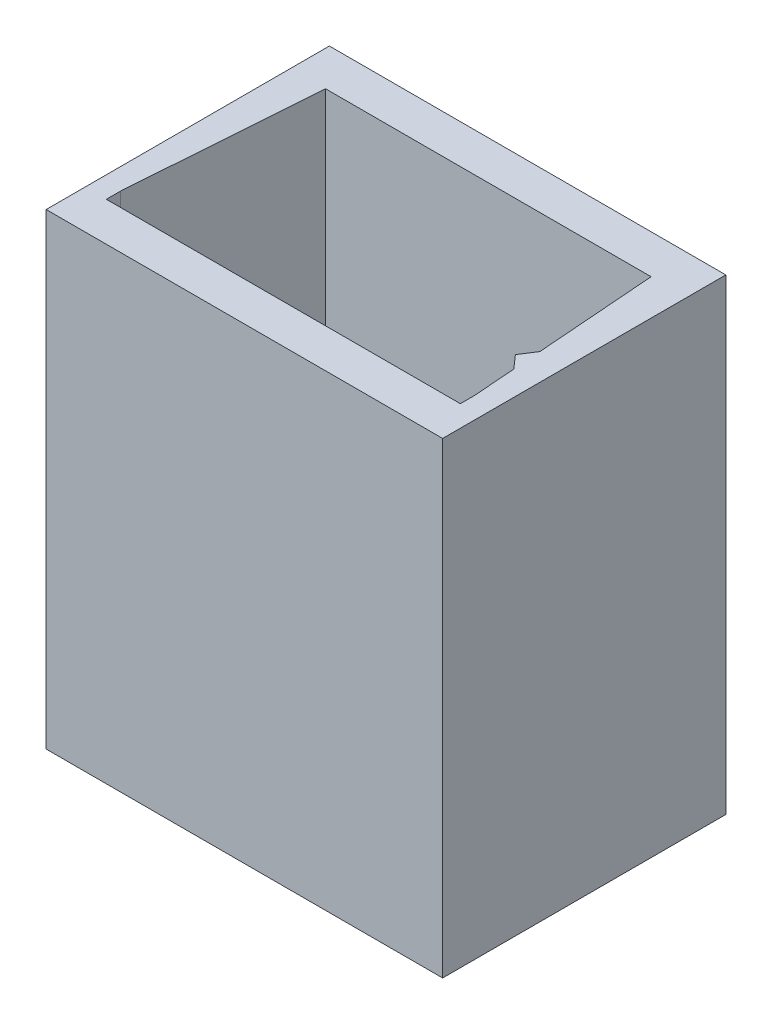
SolidWorks part; units mm, degrees
ref_plane "Plano frontal" through (0, 0, 0) normal (0, 0, 1) x (1, 0, 0)
ref_plane "Plano superior" through (0, 0, 0) normal (0, 1, 0) x (1, 0, 0)
ref_plane "Plano direito" through (0, 0, 0) normal (1, 0, 0) x (0, 0, -1)
sketch "Esboço1" plane through (0, 0, 0) normal (0, 1, 0) x (1, 0, 0)
  line L1 (-28, 20) -> (28, 20)
  line L2 (-28, 20) -> (-28, -20)
  line L3 (-28, -20) -> (28, -20)
  line L4 (28, 20) -> (28, -20)
  dimension "D1" = 56
  dimension "D2" = 40
  dimension "D3" = 20
  dimension "D4" = 28
extrude "Ressalto-extrusão1" add sketch "Esboço1" along normal blind 66
sketch "Esboço2" plane through (0, 66, 0) normal (0, 1, 0) x (1, 0, 0)
  line L0 (-25, -14.5) -> (25, -14.5)
  line L1 (25, -14.5) -> (25, -12.5)
  line L2 (25, -12.5) -> (24.5432, -6.4974)
  line L3 (24.5432, -6.4974) -> (22.8946, -4.618)
  line L4 (22.8946, -4.618) -> (24.2399, -2.5108)
  line L5 (24.2399, -2.5108) -> (22.9455, 14.5)
  line L6 (22.9455, 14.5) -> (-23.0545, 14.5)
  line L7 (-23.0545, 14.5) -> (-25, -12.5)
  line L8 (-25, -12.5) -> (-25, -14.5)
  line L9 (28, -20) -> (28, 20) construction
  line L10 (-28, -20) -> (28, -20) construction
  point P2 (-17.0422, 11.8931)
  point P10 (33.2269, 1.686)
  point P11 (20.4142, -5.3314)
  point P12 (25.9734, -2.0505)
  point P13 (24.0596, 7.2452)
  point P14 (25.9734, -5.5137)
  point P15 (20.7787, -2.6885)
  point P16 (31.6238, 0)
  point P17 (31.6238, -5.8782)
  point P18 (-19.594, -13.4424)
  point P19 (21.2344, -2.6885)
  point P22 (22.2588, 9.8881)
  point P27 (-28, -13.4424)
  dimension "D1" = 50
  dimension "D2" = 46
  dimension "D3" = 27.07
  dimension "D4" = 2
  dimension "D5" = 17.06
  dimension "D6" = 2.5
  dimension "D7" = 6.02
  dimension "D8" = 3
  dimension "D9" = 5.5
  dimension "D10" = 29
extrude "Corte-extrusão1" cut sketch "Esboço2" against normal blind 61
sketch "Esboço10" plane through (0, 0, 0) normal (0, -1, 0) x (1, 0, 0)
  line L0 (-28, -20) -> (-28, 20) construction
  line L1 (-26.7, 18.7) -> (26.7, 18.7)
  line L2 (-26.7, 18.7) -> (-26.7, -18.7)
  line L3 (-26.7, -18.7) -> (26.7, -18.7)
  line L4 (26.7, 18.7) -> (26.7, -18.7)
  line L5 (-28, 20) -> (28, 20) construction
  line L6 (28, 20) -> (28, -20) construction
  line L7 (28, -20) -> (-28, -20) construction
  dimension "D1" = 1.3
  dimension "D2" = 1.3
  dimension "D3" = 1.3
  dimension "D4" = 1.3
extrude "Corte-extrusão2" cut sketch "Esboço10" against normal blind 2.2
sketch "Esboço11" plane through (0, 2.2, 0) normal (0, -1, 0) x (-1, 0, 0)
  line L0 (28, 20) -> (28, -20) construction
  line L3 (26.7, 0) -> (-26.7, 0) construction
  line L4 (26.7, -18.7) -> (26.7, 18.7) construction
  line L5 (-26.7, 18.7) -> (-26.7, -18.7) construction
  line L6 (28, -20) -> (-28, -20) construction
  circle A0 centre (20, -12) radius 2.4
  circle A1 centre (20, -12) radius 3.255
  circle A2 centre (12, -12) radius 3.255
  circle A3 centre (12, -12) radius 2.4
  circle A4 centre (20, -4) radius 3.255
  circle A5 centre (20, -4) radius 2.4
  circle A6 centre (12, -4) radius 3.255
  circle A7 centre (12, -4) radius 2.4
  circle A8 centre (20, 4) radius 3.255
  circle A9 centre (20, 4) radius 2.4
  circle A10 centre (12, 4) radius 3.255
  circle A11 centre (12, 4) radius 2.4
  circle A12 centre (20, 12) radius 3.255
  circle A13 centre (20, 12) radius 2.4
  circle A14 centre (12, 12) radius 3.255
  circle A15 centre (12, 12) radius 2.4
  circle A16 centre (4, -12) radius 3.255
  circle A17 centre (4, -12) radius 2.4
  circle A18 centre (-4, -12) radius 3.255
  circle A19 centre (-4, -12) radius 2.4
  circle A20 centre (-12, -12) radius 3.255
  circle A21 centre (-12, -12) radius 2.4
  circle A22 centre (-20, -12) radius 3.255
  circle A23 centre (-20, -12) radius 2.4
  circle A24 centre (4, -4) radius 3.255
  circle A25 centre (4, -4) radius 2.4
  circle A26 centre (-4, -4) radius 3.255
  circle A27 centre (-4, -4) radius 2.4
  circle A28 centre (-12, -4) radius 3.255
  circle A29 centre (-12, -4) radius 2.4
  circle A30 centre (-20, -4) radius 3.255
  circle A31 centre (-20, -4) radius 2.4
  circle A32 centre (4, 4) radius 3.255
  circle A33 centre (4, 4) radius 2.4
  circle A34 centre (-4, 4) radius 3.255
  circle A35 centre (-4, 4) radius 2.4
  circle A36 centre (-12, 4) radius 3.255
  circle A37 centre (-12, 4) radius 2.4
  circle A38 centre (-20, 4) radius 3.255
  circle A39 centre (-20, 4) radius 2.4
  circle A40 centre (4, 12) radius 3.255
  circle A41 centre (4, 12) radius 2.4
  circle A42 centre (-4, 12) radius 3.255
  circle A43 centre (-4, 12) radius 2.4
  circle A44 centre (-12, 12) radius 3.255
  circle A45 centre (-12, 12) radius 2.4
  circle A46 centre (-20, 12) radius 3.255
  circle A47 centre (-20, 12) radius 2.4
  dimension "D1" = 8
  dimension "D2" = 6.51
  dimension "D3" = 4.8
  dimension "D4" = 8
  dimension "D5" = 6
  dimension "D6" = 4
extrude "Ressalto-extrusão11" add sketch "Esboço11" along normal up to surface (2.2 mm away) up to face at (0, 0, 0)
sketch "Esboço14" plane through (0, 2.2, 0) normal (0, -1, 0) x (1, 0, 0)
  line L0 (-28, 20) -> (28, 20) construction
  line L1 (-24.5, 20) -> (-23.5, 20)
  line L2 (-24.5, 20) -> (-24.5, 18.4)
  line L3 (-24.5, 18.4) -> (-23.5, 18.4)
  line L4 (-23.5, 20) -> (-23.5, 18.4)
  line L5 (-16.5, 20) -> (-15.5, 20)
  line L6 (-15.5, 20) -> (-15.5, 18.4)
  line L7 (-16.5, 18.4) -> (-15.5, 18.4)
  line L8 (-16.5, 20) -> (-16.5, 18.4)
  line L9 (-8.5, 20) -> (-7.5, 20)
  line L10 (-7.5, 20) -> (-7.5, 18.4)
  line L11 (-8.5, 18.4) -> (-7.5, 18.4)
  line L12 (-8.5, 20) -> (-8.5, 18.4)
  line L13 (-0.5, 20) -> (0.5, 20)
  line L14 (0.5, 20) -> (0.5, 18.4)
  line L15 (-0.5, 18.4) -> (0.5, 18.4)
  line L16 (-0.5, 20) -> (-0.5, 18.4)
  line L17 (7.5, 20) -> (8.5, 20)
  line L18 (8.5, 20) -> (8.5, 18.4)
  line L19 (7.5, 18.4) -> (8.5, 18.4)
  line L20 (7.5, 20) -> (7.5, 18.4)
  line L21 (15.5, 20) -> (16.5, 20)
  line L22 (16.5, 20) -> (16.5, 18.4)
  line L23 (15.5, 18.4) -> (16.5, 18.4)
  line L24 (15.5, 20) -> (15.5, 18.4)
  line L25 (23.5, 20) -> (24.5, 20)
  line L26 (24.5, 20) -> (24.5, 18.4)
  line L27 (23.5, 18.4) -> (24.5, 18.4)
  line L28 (23.5, 20) -> (23.5, 18.4)
  line L29 (-16.5, -18.4) -> (-15.5, -18.4)
  line L30 (-15.5, -18.4) -> (-15.5, -20)
  line L31 (-16.5, -20) -> (-15.5, -20)
  line L32 (-16.5, -18.4) -> (-16.5, -20)
  line L33 (-8.5, -18.4) -> (-7.5, -18.4)
  line L34 (-7.5, -18.4) -> (-7.5, -20)
  line L35 (-8.5, -20) -> (-7.5, -20)
  line L36 (-8.5, -18.4) -> (-8.5, -20)
  line L37 (-0.5, -18.4) -> (0.5, -18.4)
  line L38 (0.5, -18.4) -> (0.5, -20)
  line L39 (-0.5, -20) -> (0.5, -20)
  line L40 (-0.5, -18.4) -> (-0.5, -20)
  line L41 (7.5, -18.4) -> (8.5, -18.4)
  line L42 (8.5, -18.4) -> (8.5, -20)
  line L43 (7.5, -20) -> (8.5, -20)
  line L44 (7.5, -18.4) -> (7.5, -20)
  line L45 (15.5, -18.4) -> (16.5, -18.4)
  line L46 (16.5, -18.4) -> (16.5, -20)
  line L47 (15.5, -20) -> (16.5, -20)
  line L48 (15.5, -18.4) -> (15.5, -20)
  line L49 (23.5, -18.4) -> (24.5, -18.4)
  line L50 (24.5, -18.4) -> (24.5, -20)
  line L51 (23.5, -20) -> (24.5, -20)
  line L52 (23.5, -18.4) -> (23.5, -20)
  line L53 (-24.5, -18.4) -> (-23.5, -18.4)
  line L54 (-23.5, -18.4) -> (-23.5, -20)
  line L55 (-24.5, -20) -> (-23.5, -20)
  line L56 (-24.5, -18.4) -> (-24.5, -20)
  dimension "D1" = 3.5
  dimension "D2" = 1
  dimension "D3" = 1.6
  dimension "D4" = 7
  dimension "D5" = 2
extrude "Ressalto-extrusão13" add sketch "Esboço14" along normal blind 2.2
sketch "Esboço15" plane through (0, 2.2, 0) normal (0, -1, 0) x (1, 0, 0)
  line L0 (-28, -20) -> (-28, 20) construction
  line L1 (-28, 16.5) -> (-26.4, 16.5)
  line L2 (-28, 16.5) -> (-28, 15.5)
  line L3 (-28, 15.5) -> (-26.4, 15.5)
  line L4 (-26.4, 16.5) -> (-26.4, 15.5)
  line L5 (-28, 20) -> (28, 20) construction
  line L6 (26.4, 16.5) -> (28, 16.5)
  line L7 (28, 16.5) -> (28, 15.5)
  line L8 (26.4, 15.5) -> (28, 15.5)
  line L9 (26.4, 16.5) -> (26.4, 15.5)
  line L10 (26.4, 8.5) -> (28, 8.5)
  line L11 (28, 8.5) -> (28, 7.5)
  line L12 (26.4, 7.5) -> (28, 7.5)
  line L13 (26.4, 8.5) -> (26.4, 7.5)
  line L14 (26.4, 0.5) -> (28, 0.5)
  line L15 (28, 0.5) -> (28, -0.5)
  line L16 (26.4, -0.5) -> (28, -0.5)
  line L17 (26.4, 0.5) -> (26.4, -0.5)
  line L18 (26.4, -7.5) -> (28, -7.5)
  line L19 (28, -7.5) -> (28, -8.5)
  line L20 (26.4, -8.5) -> (28, -8.5)
  line L21 (26.4, -7.5) -> (26.4, -8.5)
  line L22 (26.4, -15.5) -> (28, -15.5)
  line L23 (28, -15.5) -> (28, -16.5)
  line L24 (26.4, -16.5) -> (28, -16.5)
  line L25 (26.4, -15.5) -> (26.4, -16.5)
  line L26 (-28, 8.5) -> (-26.4, 8.5)
  line L27 (-26.4, 8.5) -> (-26.4, 7.5)
  line L28 (-28, 7.5) -> (-26.4, 7.5)
  line L29 (-28, 8.5) -> (-28, 7.5)
  line L30 (-28, 0.5) -> (-26.4, 0.5)
  line L31 (-26.4, 0.5) -> (-26.4, -0.5)
  line L32 (-28, -0.5) -> (-26.4, -0.5)
  line L33 (-28, 0.5) -> (-28, -0.5)
  line L34 (-28, -7.5) -> (-26.4, -7.5)
  line L35 (-26.4, -7.5) -> (-26.4, -8.5)
  line L36 (-28, -8.5) -> (-26.4, -8.5)
  line L37 (-28, -7.5) -> (-28, -8.5)
  line L38 (-28, -15.5) -> (-26.4, -15.5)
  line L39 (-26.4, -15.5) -> (-26.4, -16.5)
  line L40 (-28, -16.5) -> (-26.4, -16.5)
  line L41 (-28, -15.5) -> (-28, -16.5)
  dimension "D1" = 1
  dimension "D2" = 1.6
  dimension "D3" = 3.5
  dimension "D4" = 2
  dimension "D5" = 5
extrude "Ressalto-extrusão14" add sketch "Esboço15" along normal blind 2.2
